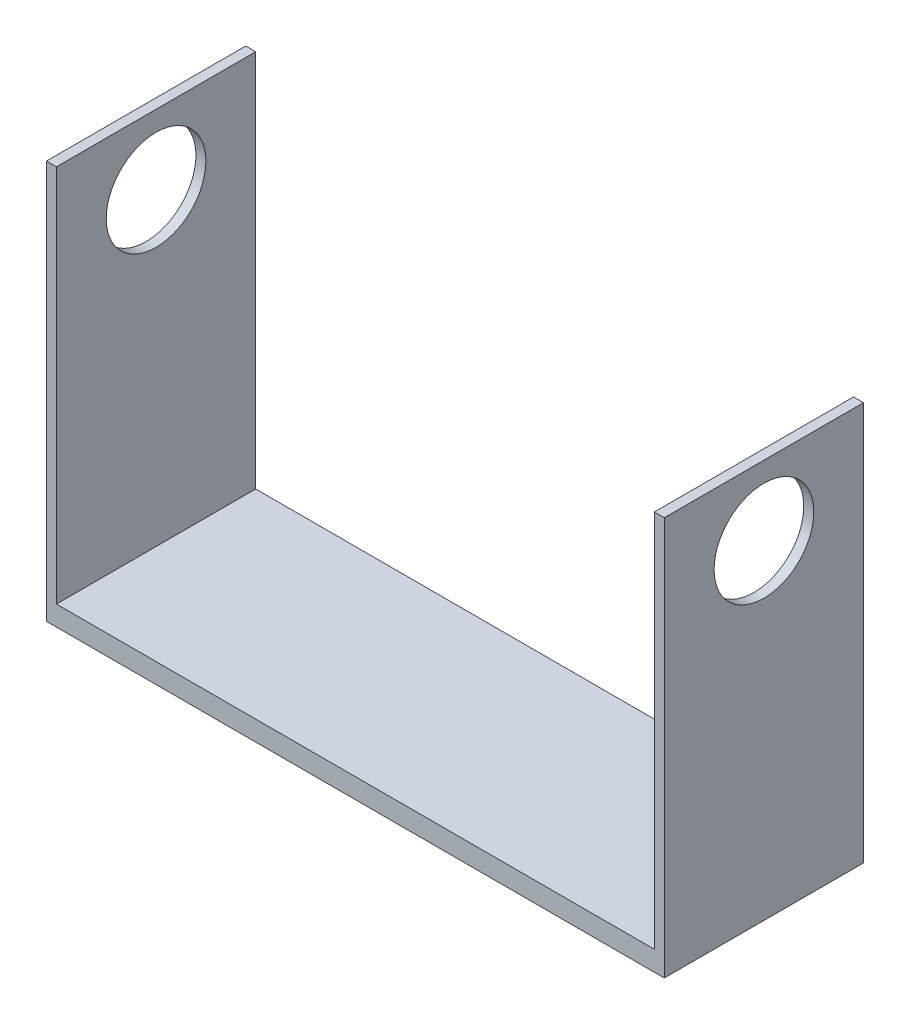
SolidWorks part; units mm, degrees
ref_plane "Front Plane" through (0, 0, 0) normal (0, 0, 1) x (1, 0, 0)
ref_plane "Top Plane" through (0, 0, 0) normal (0, 1, 0) x (1, 0, 0)
ref_plane "Right Plane" through (0, 0, 0) normal (1, 0, 0) x (0, 0, -1)
sketch "Sketch1" plane through (0, 0, 0) normal (0, 1, 0) x (1, 0, 0)
  line L1 (-150, -50) -> (150, -50)
  line L2 (-150, -50) -> (-150, 50)
  line L3 (-150, 50) -> (150, 50)
  line L4 (150, -50) -> (150, 50)
  line L5 (-150, -50) -> (150, 50) construction
  line L6 (-150, 50) -> (150, -50) construction
  point P0 (0, 0)
  dimension "D1" = 300
  dimension "D2" = 100
extrude "Boss-Extrude1" add sketch "Sketch1" along normal blind 10
sketch "Sketch2" plane through (150, 0, 0) normal (1, 0, 0) x (0, 0, -1)
  line L1 (-50, 0) -> (50, 0)
  line L2 (-50, 0) -> (-50, 200)
  line L3 (-50, 200) -> (50, 200)
  line L4 (50, 0) -> (50, 200)
  dimension "D1" = 200
extrude "Boss-Extrude2" add sketch "Sketch2" along normal blind 5
sketch "Sketch3" plane through (-150, 0, 0) normal (-1, 0, 0) x (0, 0, 1)
  line L1 (-50, 0) -> (50, 0)
  line L2 (-50, 0) -> (-50, 200)
  line L3 (-50, 200) -> (50, 200)
  line L4 (50, 0) -> (50, 200)
extrude "Boss-Extrude3" add sketch "Sketch3" along normal blind 5
sketch "Sketch4" plane through (-155, 0, 0) normal (-1, 0, 0) x (0, 0, 1)
  line L0 (50, 200) -> (-50, 200) construction
  line L1 (-50, 200) -> (-50, 0) construction
  circle A0 centre (0, 165) radius 25
  point P2 (0, 0)
  dimension "D1" = 50
  dimension "D2" = 35
  dimension "D3" = 50
extrude "Cut-Extrude1" cut sketch "Sketch4" against normal up to surface (310 mm away) up to face at (155, 100, 0)
